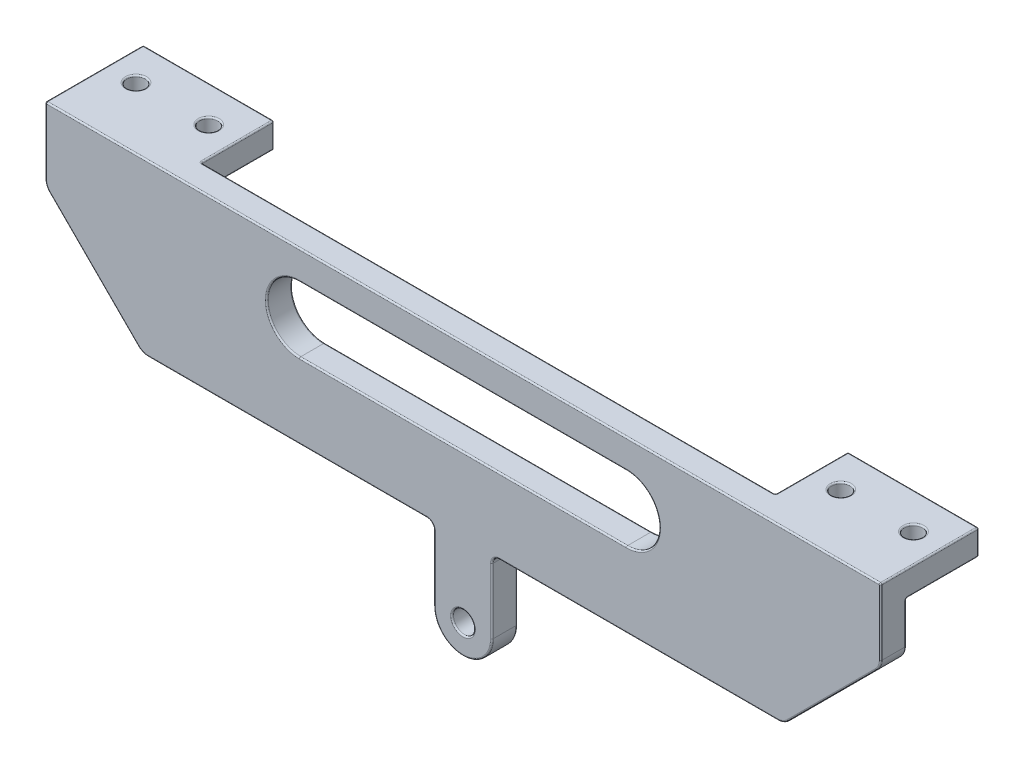
SolidWorks part; units mm, degrees
ref_plane "Front Plane" through (0, 0, 0) normal (0, 0, 1) x (1, 0, 0)
ref_plane "Top Plane" through (0, 0, 0) normal (0, 1, 0) x (1, 0, 0)
ref_plane "Right Plane" through (0, 0, 0) normal (1, 0, 0) x (0, 0, -1)
sketch "Sketch1" plane through (0, 0, 0) normal (0, 0, 1) x (1, 0, 0)
  line L0 (-100, 0) -> (100, 0) construction
  line L1 (-100, 0) -> (0, 100) construction
  line L2 (0, 100) -> (100, 0) construction
  line L3 (0, 0) -> (-50, 50) construction
  line L4 (-40, 60) -> (40, 60) construction
  line L5 (0, 100) -> (0, 60) construction
  circle A0 centre (-100, 0) radius 20
  circle A1 centre (0, 0) radius 20
  circle A2 centre (100, 0) radius 20
  point P3 (0, 0)
  dimension "D5" = 40
  dimension "D1" = 200
  dimension "D2" = 90
  dimension "D3" = 90
  dimension "D4" = 80
sketch "Sketch2" plane through (0, 0, 0) normal (0, 0, 1) x (1, 0, 0)
  line L0 (-56.5165, 43.4835) -> (-40, 60) construction
  line L1 (-100, 0) -> (0, 100) construction
  line L2 (-40, 60) -> (40, 60) construction
  line L3 (40, 60) -> (86.565, 13.435) construction
  line L4 (0, 100) -> (100, 0) construction
  line L5 (-49.4454, 36.4124) -> (-35.8579, 50)
  line L6 (-35.8579, 50) -> (35.8579, 50)
  line L7 (35.8579, 50) -> (79.4939, 6.364)
  line L8 (-63.5876, 50.5546) -> (-44.1421, 70)
  line L9 (-44.1421, 70) -> (44.1421, 70)
  line L10 (44.1421, 70) -> (93.636, 20.5061)
  line L11 (-63.5876, 50.5546) -> (-49.4454, 36.4124)
  line L12 (79.4939, 6.364) -> (93.636, 20.5061)
  line L13 (86.565, 13.435) -> (100, 0) construction
  line L14 (81.9688, 8.8388) -> (95.4038, -4.5962)
  line L15 (91.1612, 18.0312) -> (104.5962, 4.5962)
  line L16 (75.9584, 9.8995) -> (90.1005, 24.0416) construction
  line L17 (0, 100) -> (0, 60) construction
  line L18 (-3.4532, 85.4203) -> (-6, 70)
  line L19 (3.4532, 85.4203) -> (6, 70)
  circle A0 centre (100, 0) radius 3.5
  circle A1 centre (100, 0) radius 10 construction
  arc A2 (95.4038, -4.5962) -> (104.5962, 4.5962) centre (100, 0) ccw
  circle A3 centre (79.4939, 13.435) radius 1
  circle A4 centre (86.565, 20.5061) radius 1
  circle A5 centre (0, 60) radius 1.5
  circle A6 centre (0, 84.85) radius 1.5
  arc A7 (3.4532, 85.4203) -> (-3.4532, 85.4203) centre (0, 84.85) ccw
  circle A8 centre (-50, 50) radius 1.5
  circle A9 centre (0, 84.85) radius 3.5 construction
  point P42 (0, 70)
  point P46 (3.5, 82)
  dimension "D4" = 20
  dimension "D5" = 7
  dimension "D6" = 3
  dimension "D9" = 2
  dimension "D12" = 3
  dimension "D17" = 3
  dimension "D3" = 27.5
  dimension "D7" = 19
  dimension "D8" = 10
  dimension "D10" = 5
  dimension "D11" = 5
  dimension "D13" = 14.85
  dimension "D15" = 6
  dimension "D16" = 6
  dimension "D1" = 10
  dimension "D2" = 10
  dimension "D14" = 2
sketch "Sketch3" plane through (0, 0, 0) normal (0, 0, 1) x (1, 0, 0)
  line L0 (-100, 0) -> (-50, 50) construction
  line L1 (-50, 50) -> (-13.435, 13.435) construction
  line L2 (-79.4939, 6.364) -> (-50, 35.8579)
  line L3 (-50, 35.8579) -> (-20.5061, 6.364)
  line L4 (-93.636, 20.5061) -> (-50, 64.1421)
  line L5 (-50, 64.1421) -> (-6.364, 20.5061)
  line L6 (-93.636, 20.5061) -> (-79.4939, 6.364)
  line L7 (-20.5061, 6.364) -> (-6.364, 20.5061)
  line L8 (-107.0711, 7.0711) -> (-50, 64.1421) construction
  line L9 (-92.9289, -7.0711) -> (-50, 35.8579) construction
  line L10 (-104.534, 4.6576) -> (-90.9809, 17.8509)
  line L11 (-81.9688, 8.8388) -> (-95.4038, -4.5962)
  line L12 (-18.0312, 8.8388) -> (-4.5962, -4.5962)
  line L13 (-8.8388, 18.0312) -> (4.5962, 4.5962)
  line L14 (-90.1005, 24.0416) -> (-75.9584, 9.8995) construction
  line L15 (-24.0416, 9.8995) -> (-9.8995, 24.0416) construction
  circle A0 centre (-100, 0) radius 10 construction
  circle A1 centre (-100, 0) radius 3.5
  circle A2 centre (0, 0) radius 10 construction
  circle A3 centre (0, 0) radius 3.5
  arc A4 (-104.534, 4.6576) -> (-95.4038, -4.5962) centre (-100, 0) ccw
  arc A5 (-4.5962, -4.5962) -> (4.5962, 4.5962) centre (0, 0) ccw
  circle A6 centre (-100, 0) radius 20 construction
  circle A7 centre (-86.565, 20.5061) radius 1
  circle A8 centre (-100, 0) radius 6.5 construction
  circle A9 centre (0, 0) radius 6.5 construction
  circle A10 centre (-79.4939, 13.435) radius 1
  circle A11 centre (-20.5061, 13.435) radius 1
  circle A12 centre (-13.435, 20.5061) radius 1
  point P23 (-86.565, 13.435)
  point P29 (-93.5, 0)
  point P31 (6.5, 0)
  dimension "D1" = 20
  dimension "D2" = 7
  dimension "D8" = 2
  dimension "D10" = 5
  dimension "D6" = 19
  dimension "D7" = 19
  dimension "D9" = 5
  dimension "D11" = 5
  dimension "D12" = 5
  dimension "D3" = 3
  dimension "D4" = 10
  dimension "D5" = 10
sketch "Sketch4" plane through (0, 0, 0) normal (0, 0, 1) x (1, 0, 0)
  line L0 (-57.5, 93.3579) -> (57.5, 93.3579)
  line L1 (57.5, 93.3579) -> (57.5, 83.3579)
  line L2 (57.5, 83.3579) -> (44.1421, 70)
  line L3 (44.1421, 70) -> (4, 70)
  line L4 (-44.1421, 70) -> (-57.5, 83.3579)
  line L5 (-57.5, 83.3579) -> (-57.5, 93.3579)
  line L6 (-4, 60) -> (-4, 70)
  line L7 (4, 60) -> (4, 70)
  line L8 (-22.5, 84.8579) -> (22.5, 84.8579) construction
  line L9 (-22.5, 89.3579) -> (22.5, 89.3579)
  line L10 (-22.5, 80.3579) -> (22.5, 80.3579)
  line L11 (-63.5876, 50.5546) -> (-44.1421, 70) construction
  line L12 (-4, 70) -> (-44.1421, 70)
  circle A0 centre (0, 60) radius 1.5 construction
  circle A1 centre (0, 60) radius 1.5
  arc A2 (-4, 60) -> (4, 60) centre (0, 60) ccw
  arc A3 (-22.5, 89.3579) -> (-22.5, 80.3579) centre (-22.5, 84.8579) ccw
  circle A4 centre (0, 60) radius 4 construction
  arc A5 (22.5, 80.3579) -> (22.5, 89.3579) centre (22.5, 84.8579) ccw
  point P10 (4, 60)
  point P12 (0, 93.3579)
  point P20 (0, 84.8579)
  dimension "D7" = 4.5
  dimension "D1" = 115
  dimension "D2" = 10
  dimension "D4" = 9
  dimension "D5" = 45
  dimension "D6" = 4
  dimension "D3" = 2.5
extrude "Boss-Extrude1" add sketch "Sketch4" along normal blind 3.5
sketch "Sketch5" plane through (0, 93.3579, 0) normal (0, 1, 0) x (1, 0, 0)
  line L0 (-57.5, 5) -> (-39.5, 5) construction
  line L1 (-57.5, 0) -> (-39.5, 0)
  line L2 (-57.5, 0) -> (-57.5, 10)
  line L3 (-57.5, 10) -> (-39.5, 10)
  line L4 (-39.5, 0) -> (-39.5, 10)
  line L5 (-48.5, 10) -> (-48.5, 0) construction
  line L6 (0, 0) -> (0, 22.8188) construction
  line L7 (48.5, 10) -> (48.5, 0) construction
  line L8 (57.5, 5) -> (39.5, 5) construction
  line L9 (39.5, 0) -> (39.5, 10)
  line L10 (57.5, 10) -> (39.5, 10)
  line L11 (57.5, 0) -> (57.5, 10)
  line L12 (57.5, 0) -> (39.5, 0)
  circle A0 centre (-53.5, 5) radius 1.25
  circle A1 centre (-43.5, 5) radius 1.25
  circle A2 centre (43.5, 5) radius 1.25
  circle A3 centre (53.5, 5) radius 1.25
  dimension "D4" = 2.5
  dimension "D1" = 18
  dimension "D2" = 10
  dimension "D3" = 10
extrude "Boss-Extrude2" add sketch "Sketch5" against normal blind 3.5
fillet "Fillet1" radius 2 4 edges at (57.5, 83.3579, 1.75) (44.1421, 70, 1.75) (-44.1421, 70, 1.75) (-57.5, 83.3579, 1.75)
fillet "Fillet2" radius 1 2 edges at (-4, 70, 1.75) (4, 70, 1.75)
fillet "Fillet3" radius 0.2 70 edges at (39.5, 91.6079, 0) (39.5, 91.6079, -10) (57.5, 91.6079, -10) (39.5, 89.8579, -5) (48.5, 89.8579, -10) (57.5, 89.8579, -5) (48.5, 89.8579, 0) (39.5, 93.3579, -5) (48.5, 93.3579, -10) (43.5, 89.8579, -6.25) (43.5, 93.3579, -6.25) (53.5, 89.8579, -6.25) (53.5, 93.3579, -6.25) (-43.5, 93.3579, -3.75) (-43.5, 89.8579, -3.75) (-53.5, 93.3579, -3.75) (-53.5, 89.8579, -3.75) (-39.5, 93.3579, -5) (-39.5, 89.8579, -5) (-48.5, 93.3579, -10) (-48.5, 89.8579, -10) (-57.5, 89.8579, -5) (-48.5, 89.8579, 0) (-39.5, 91.6079, 0) (-39.5, 91.6079, -10) (-57.5, 91.6079, -10) (-27, 84.8579, 0) (0, 80.3579, 0) (27, 84.8579, 0) (0, 89.3579, 0) (-27, 84.8579, 3.5) (0, 80.3579, 3.5) (27, 84.8579, 3.5) (0, 89.3579, 3.5) (1.5, 60, 0) (1.5, 60, 3.5) (-57.5, 87.0221, 0) (-50.8211, 76.6789, 0) (-24.1569, 70, 0) (-4, 64.5, 0) (0, 56, 0) (4, 64.5, 0) (24.1569, 70, 0) (50.8211, 76.6789, 0) (57.5, 87.0221, 0) (-57.5, 88.7721, 3.5) (-50.8211, 76.6789, 3.5) (-24.1569, 70, 3.5) (-4, 64.5, 3.5) (0, 56, 3.5) (4, 64.5, 3.5) (24.1569, 70, 3.5) (50.8211, 76.6789, 3.5) (57.5, 88.7721, 3.5) (0, 93.3579, 3.5) (-57.5, 93.3579, -3.25) (57.5, 93.3579, -3.25) (-57.3478, 83.4209, 0) (-44.0791, 70.1522, 0) (44.0791, 70.1522, 0) (57.3478, 83.4209, 0) (-57.3478, 83.4209, 3.5) (-44.0791, 70.1522, 3.5) (44.0791, 70.1522, 3.5) (57.3478, 83.4209, 3.5) (-4.2929, 69.7071, 0) (-4.2929, 69.7071, 3.5) (4.2929, 69.7071, 0) (4.2929, 69.7071, 3.5) (0, 93.3579, 0)
